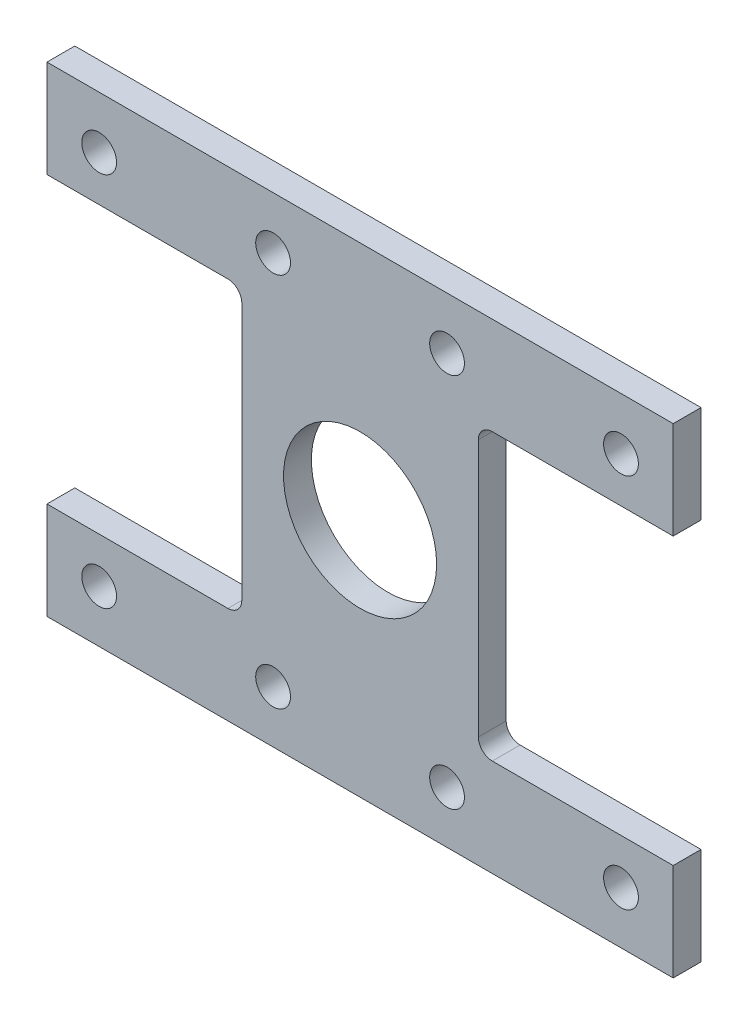
SolidWorks part; units mm, degrees
material "Thornel Mat VMA"
ref_plane "前视基准面" through (0, 0, 0) normal (0, 0, 1) x (1, 0, 0)
ref_plane "上视基准面" through (0, 0, 0) normal (0, 1, 0) x (1, 0, 0)
ref_plane "右视基准面" through (0, 0, 0) normal (1, 0, 0) x (0, 0, -1)
sketch "草图1" plane through (0, 0, 0) normal (0, 0, 1) x (1, 0, 0)
  line L0 (0, 0) -> (0, 69) construction
  line L1 (45, 0) -> (-45, 0)
  line L2 (-45, 0) -> (-45, 14)
  line L3 (45, 0) -> (45, 14)
  line L4 (-45, 14) -> (-17, 14)
  line L5 (45, 14) -> (17, 14)
  line L6 (-17, 14) -> (-17, 55)
  line L7 (17, 14) -> (17, 55)
  line L8 (-17, 55) -> (-45, 55)
  line L9 (17, 55) -> (45, 55)
  line L10 (-45, 55) -> (-45, 69)
  line L11 (45, 55) -> (45, 69)
  line L12 (-45, 69) -> (45, 69)
  dimension "D1" = 90
  dimension "D2" = 69
  dimension "D3" = 34
  dimension "D4" = 14
  dimension "D5" = 14
extrude "凸台-拉伸1" add sketch "草图1" along normal blind 4
fillet "圆角1" radius 2 4 edges at (-17, 14, 2) (17, 14, 2) (-17, 55, 2) (17, 55, 2)
sketch "草图2" plane through (0, 0, 4) normal (0, 0, 1) x (1, 0, 0)
  line L0 (-50, 61.5) -> (50, 61.5) construction
  line L3 (50, 7.5) -> (-50, 7.5) construction
  line L6 (0, 69) -> (0, 0) construction
  line L7 (45, 69) -> (-45, 69) construction
  line L8 (-45, 0) -> (45, 0) construction
  circle A0 centre (-37.5, 61.5) radius 2.5
  circle A1 centre (37.5, 61.5) radius 2.5
  circle A2 centre (-12.5, 61.5) radius 2.5
  circle A3 centre (12.5, 61.5) radius 2.5
  circle A4 centre (-37.5, 7.5) radius 2.5
  circle A5 centre (37.5, 7.5) radius 2.5
  circle A6 centre (-12.5, 7.5) radius 2.5
  circle A7 centre (12.5, 7.5) radius 2.5
  dimension "D1" = 5
  dimension "D2" = 12.5
  dimension "D3" = 25
  dimension "D4" = 7.5
  dimension "D5" = 7.5
extrude "切除-拉伸1" cut sketch "草图2" against normal through all
sketch "草图3" plane through (0, 0, 4) normal (0, 0, 1) x (1, 0, 0)
  line L0 (0, 69) -> (0, 0) construction
  line L1 (45, 69) -> (-45, 69) construction
  circle A0 centre (0, 34.5) radius 11
  dimension "D1" = 22
extrude "切除-拉伸2" cut sketch "草图3" against normal through all
